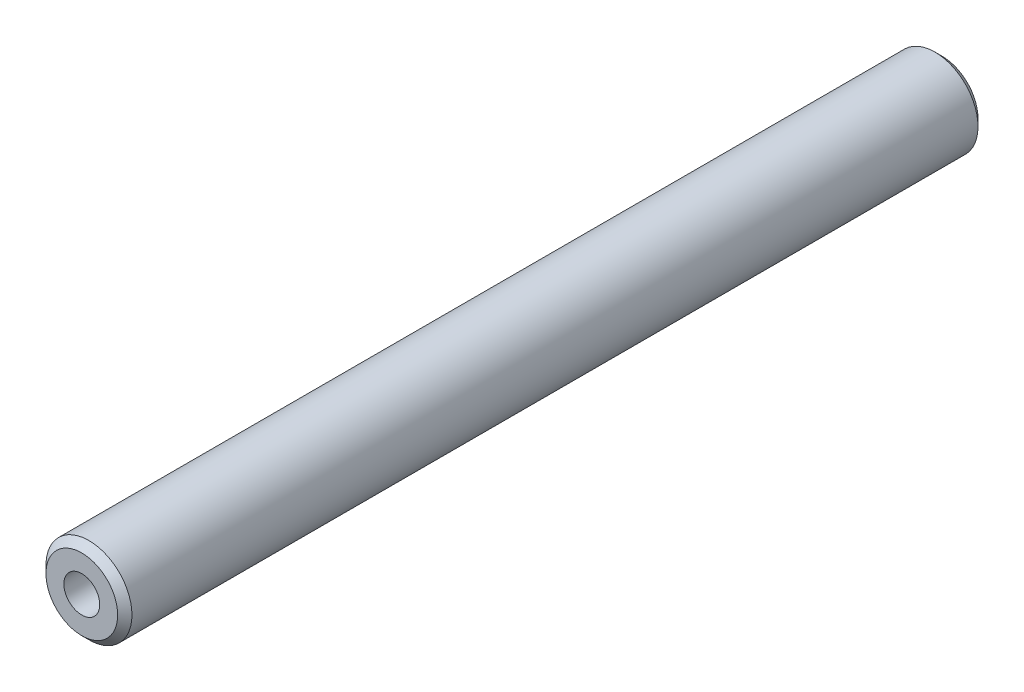
SolidWorks part; units mm, degrees
material "KS26"
ref_plane "正面" through (0, 0, 0) normal (0, 0, 1) x (1, 0, 0)
ref_plane "平面" through (0, 0, 0) normal (0, 1, 0) x (1, 0, 0)
ref_plane "右側面" through (0, 0, 0) normal (1, 0, 0) x (0, 0, -1)
sketch "ｽｹｯﾁ2" plane through (0, 0, 0) normal (0, 0, 1) x (1, 0, 0)
  circle A0 centre (0, 0) radius 3
  dimension "D1" = 6
extrude "ﾎﾞｽ - 押し出し1" add sketch "ｽｹｯﾁ2" along normal mid plane 60
hole_wizard "M3 ねじ穴1" positions "ｽｹｯﾁ3" profile "ｽｹｯﾁ4" tap size "M3" standard "JIS"
sketch "ｽｹｯﾁ3" plane through (0, 0, 30) normal (0, 0, 1) x (1, 0, 0)
  point P0 (0, 0)
sketch "ｽｹｯﾁ4" plane through (0, 0, 30) normal (1, 0, 0) x (0, -1, 0)
  line L0 (0, 0) -> (0, 9.2511)
  line L1 (0, 9.2511) -> (1.25, 8.5)
  line L2 (1.25, 8.5) -> (1.25, 0)
  line L5 (1.25, 0) -> (0, 0)
  line L10 (0, 9.2511) -> (-1.25, 8.5) construction
  line L11 (0, -6.35) -> (0, 107.95) construction
  dimension "ねじ下穴ﾄﾞﾘﾙ直径" = 2.5
  dimension "ねじ下穴ﾄﾞﾘﾙの深さ" = 8.5
  dimension "ﾄﾞﾘﾙ角度" = 118
cosmetic thread "穴のねじ山1"
mirror "ﾐﾗｰ1" about plane through (0, 0, 0) normal (0, 0, 1) of "M3 ねじ穴1"
chamfer "面取り1" distance 0.5 angle 45 2 edges at (3, 0, -30) (3, 0, 30)
